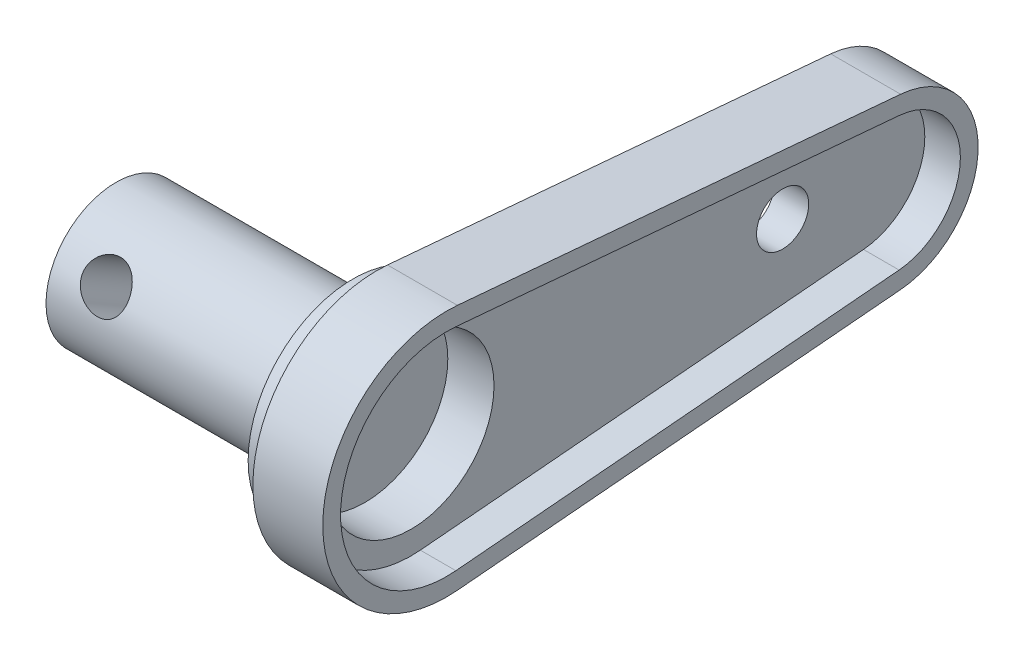
SolidWorks part; units mm, degrees
ref_plane "Front Plane" through (0, 0, 0) normal (0, 0, 1) x (1, 0, 0)
ref_plane "Top Plane" through (0, 0, 0) normal (0, 1, 0) x (1, 0, 0)
ref_plane "Right Plane" through (0, 0, 0) normal (1, 0, 0) x (0, 0, -1)
sketch "Sketch1" plane through (0, 0, 0) normal (1, 0, 0) x (0, 0, -1)
  line L0 (0, -5.3086) -> (0, 5.3086) construction
  line L1 (28.0924, -3.3356) -> (28.0924, 3.3356) construction
  line L2 (24.7695, 3.6263) -> (5.7713, 5.2884)
  line L3 (24.7695, -3.6263) -> (5.7713, -5.2884)
  line L4 (-3.2673, 0) -> (38.3183, 0) construction
  line L6 (0, -10.9604) -> (0, 17.3539) construction
  line L8 (28.0924, -10.9604) -> (28.0924, 17.3539) construction
  line L9 (5.3086, -5.3086) -> (5.3086, 5.3086) construction
  arc A0 (5.7713, 5.2884) -> (5.7713, -5.2884) centre (5.3086, 0) ccw
  arc A1 (24.7695, -3.6263) -> (24.7695, 3.6263) centre (24.4523, 0) ccw
  dimension "D2" = 10.6172
  dimension "D3" = 5
  dimension "D5" = 5
  dimension "D1" = 28.0924
  dimension "D4" = 5.3086
extrude "Boss-Extrude1" add sketch "Sketch1" along normal blind 2.9972
sketch "Sketch2" plane through (0, 0, 0) normal (-1, 0, 0) x (0, 0, 1)
  circle A0 centre (-5.3086, 0) radius 3
  dimension "D1" = 6
extrude "Boss-Extrude2" add sketch "Sketch2" along normal blind 11.176
sketch "Sketch3" plane through (0, 0, 0) normal (-1, 0, 0) x (0, 0, 1)
  circle A0 centre (-5.3086, 0) radius 4.4958
  dimension "D1" = 8.9916
extrude "Boss-Extrude3" add sketch "Sketch3" along normal blind 1.016
sketch "Sketch4" plane through (2.9972, 0, 0) normal (1, 0, 0) x (0, 0, -1)
  line L0 (24.7695, 3.6263) -> (5.7713, 5.2884) construction
  line L1 (5.7713, -5.2884) -> (24.7695, -3.6263) construction
  line L2 (24.7695, 3.6263) -> (5.7713, 5.2884) construction
  line L3 (5.7713, -5.2884) -> (24.7695, -3.6263) construction
  line L4 (24.7031, 2.8672) -> (5.7049, 4.5293)
  line L5 (5.7049, -4.5293) -> (24.7031, -2.8672)
  arc A0 (5.7713, 5.2884) -> (5.7713, -5.2884) centre (5.3086, 0) ccw construction
  arc A1 (24.7695, -3.6263) -> (24.7695, 3.6263) centre (24.4523, 0) ccw construction
  arc A2 (5.7713, 5.2884) -> (5.7713, -5.2884) centre (5.3086, 0) ccw construction
  arc A3 (24.7695, -3.6263) -> (24.7695, 3.6263) centre (24.4523, 0) ccw construction
  arc A4 (5.7049, 4.5293) -> (5.7049, -4.5293) centre (5.3086, 0) ccw
  arc A5 (24.7031, -2.8672) -> (24.7031, 2.8672) centre (24.4523, 0) ccw
  dimension "D1" = 0.762
extrude "Cut-Extrude1" cut sketch "Sketch4" against normal blind 1.524
sketch "Sketch5" plane through (1.4732, 0, 0) normal (1, 0, 0) x (0, 0, -1)
  circle A0 centre (5.3086, 0) radius 3.556
  dimension "D1" = 7.112
extrude "Cut-Extrude2" cut sketch "Sketch5" against normal blind 1.9812
sketch "Sketch6" plane through (1.4732, 0, 0) normal (1, 0, 0) x (0, 0, -1)
  line L0 (-1.2213, 0) -> (32.579, 0) construction
  line L1 (28.0924, 0) -> (28.0924, 4.7193) construction
  line L2 (22.352, 0) -> (22.352, 4.7193) construction
  line L3 (21.2344, 0) -> (21.2344, 4.7193) construction
  arc A0 (24.7695, -3.6263) -> (24.7695, 3.6263) centre (24.4523, 0) ccw construction
  circle A1 centre (21.2344, 0) radius 1.1176
  dimension "D3" = 2.2352
  dimension "D1" = 5.7404
  dimension "D2" = 1.1176
extrude "Cut-Extrude3" cut sketch "Sketch6" against normal through all
sketch "Sketch8" plane through (2.9972, 0, 0) normal (1, 0, 0) x (0, 0, -1)
  line L0 (5.3086, 0) -> (24.4523, 0) construction
sketch "Sketch9" plane through (0, -4.097, -7.0962) normal (0, -0.5, -0.866) x (-1, 0, 0)
  circle A0 centre (9.0228, 2.6543) radius 0.9906 construction
  circle A1 centre (9.0228, 2.6543) radius 0.9906
extrude "Cut-Extrude4" cut sketch "Sketch9" against normal blind 10.16
